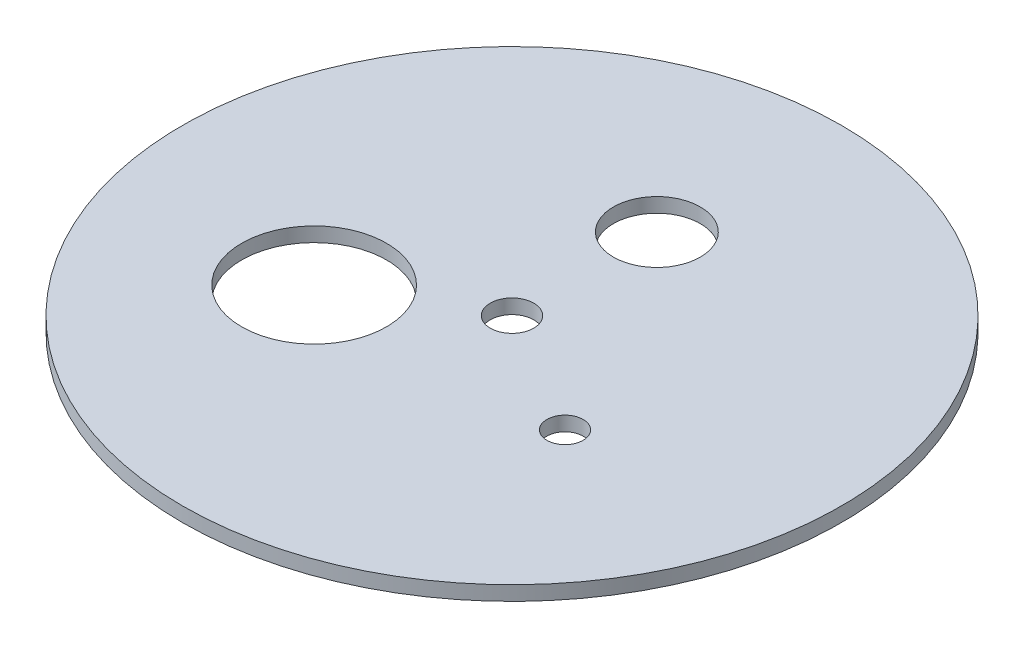
SolidWorks part; units mm, degrees
ref_plane "Front Plane" through (0, 0, 0) normal (0, 0, 1) x (1, 0, 0)
ref_plane "Top Plane" through (0, 0, 0) normal (0, 1, 0) x (1, 0, 0)
ref_plane "Right Plane" through (0, 0, 0) normal (1, 0, 0) x (0, 0, -1)
sketch "Sketch1" plane through (0, 0, 0) normal (0, 1, 0) x (1, 0, 0)
  line L0 (0, 20) -> (0, 0) construction
  line L1 (0, 0) -> (-17.3205, -10) construction
  line L2 (0, 0) -> (17.3205, -10) construction
  circle A0 centre (0, 0) radius 45.5
  circle A1 centre (0, 20) radius 6
  circle A2 centre (-17.3205, -10) radius 10
  circle A3 centre (17.3205, -10) radius 2.5
  circle A4 centre (0, 0) radius 3
  point P3 (0, 20)
  point P8 (17.3205, -10)
  point P9 (-17.3205, -10)
  point P10 (0, 0)
  dimension "D1" = 91
  dimension "D4" = 12
  dimension "D5" = 20
  dimension "D6" = 6
  dimension "D2" = 20
  dimension "D3" = 3
extrude "Boss-Extrude1" add sketch "Sketch1" along normal blind 2
